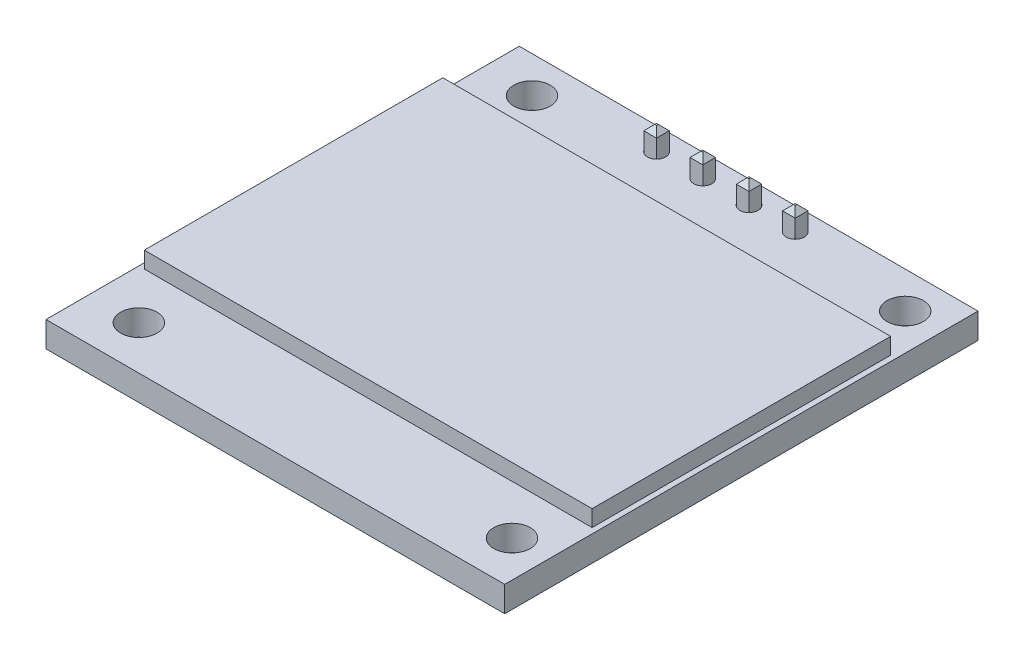
SolidWorks part; units mm, degrees
ref_plane "Front Plane" through (0, 0, 0) normal (0, 0, 1) x (1, 0, 0)
ref_plane "Top Plane" through (0, 0, 0) normal (0, 1, 0) x (1, 0, 0)
ref_plane "Right Plane" through (0, 0, 0) normal (1, 0, 0) x (0, 0, -1)
sketch "Sketch1" plane through (0, 0, 0) normal (0, 1, 0) x (1, 0, 0)
  line L0 (-3.81, 11.75) -> (3.81, 11.75) construction
  line L1 (-12.6, 13) -> (12.6, 13)
  line L2 (-12.6, 13) -> (-12.6, -13)
  line L3 (-12.6, -13) -> (12.6, -13)
  line L4 (12.6, 13) -> (12.6, -13)
  line L5 (-12.6, 13) -> (12.6, -13) construction
  line L6 (-12.6, -13) -> (12.6, 13) construction
  circle A0 centre (-9.9, 11) radius 1
  circle A1 centre (10.6, 11) radius 1
  circle A2 centre (-9.9, -10.6) radius 1
  circle A3 centre (10.6, -10.6) radius 1
  circle A4 centre (-3.81, 11.75) radius 0.5
  circle A5 centre (-1.27, 11.75) radius 0.5
  circle A6 centre (1.27, 11.75) radius 0.5
  circle A7 centre (3.81, 11.75) radius 0.5
  point P0 (0, 0)
  dimension "D3" = 2
  dimension "D8" = 1
  dimension "D10" = 4
  dimension "D1" = 25.2
  dimension "D2" = 26
  dimension "D4" = 20.5
  dimension "D5" = 21.6
  dimension "D6" = 2
  dimension "D7" = 2
  dimension "D9" = 1.25
  dimension "D11" = 3.81
extrude "Boss-Extrude1" add sketch "Sketch1" along normal blind 1.4
sketch "Sketch2" plane through (0, 1.4, 0) normal (0, 1, 0) x (1, 0, 0)
  line L0 (12.6, 13) -> (-12.6, 13) construction
  line L5 (-12.3, 8.5) -> (12.3, 8.5)
  line L6 (-12.3, 8.5) -> (-12.3, -7.9)
  line L7 (-12.3, -7.9) -> (12.3, -7.9)
  line L8 (12.3, 8.5) -> (12.3, -7.9)
  point P4 (0, 8.5)
  dimension "D1" = 16.4
  dimension "D2" = 24.6
  dimension "D3" = 4.5
extrude "Boss-Extrude2" add sketch "Sketch2" along normal blind 0.9
sketch "Sketch3" plane through (0, 0, 0) normal (0, -1, 0) x (1, 0, 0)
  line L0 (12.6, -13) -> (-12.6, -13) construction
  line L1 (5.08, -13.02) -> (-5.08, -13.02)
  line L2 (5.08, -13.02) -> (5.08, -10.48)
  line L3 (5.08, -10.48) -> (-5.08, -10.48)
  line L4 (-5.08, -13.02) -> (-5.08, -10.48)
  point P4 (0, -13.02)
  point P5 (5.08, -11.75)
  dimension "D1" = 10.16
  dimension "D2" = 2.54
  dimension "D3" = 1.25
extrude "Boss-Extrude3" add sketch "Sketch3" along normal blind 1
sketch "Sketch4" plane through (0, 0, 0) normal (0, -1, 0) x (1, 0, 0)
  line L0 (12.6, -13) -> (5.08, -13) construction
  line L1 (-3.46, -12.1) -> (-4.16, -12.1)
  line L2 (-3.46, -12.1) -> (-3.46, -11.4)
  line L3 (-3.46, -11.4) -> (-4.16, -11.4)
  line L4 (-4.16, -12.1) -> (-4.16, -11.4)
  line L5 (-0.92, -12.1) -> (-1.62, -12.1)
  line L6 (-0.92, -12.1) -> (-0.92, -11.4)
  line L7 (-0.92, -11.4) -> (-1.62, -11.4)
  line L8 (-1.62, -12.1) -> (-1.62, -11.4)
  line L9 (1.62, -12.1) -> (0.92, -12.1)
  line L10 (1.62, -12.1) -> (1.62, -11.4)
  line L11 (1.62, -11.4) -> (0.92, -11.4)
  line L12 (0.92, -12.1) -> (0.92, -11.4)
  line L13 (4.16, -12.1) -> (3.46, -12.1)
  line L14 (4.16, -12.1) -> (4.16, -11.4)
  line L15 (4.16, -11.4) -> (3.46, -11.4)
  line L16 (3.46, -12.1) -> (3.46, -11.4)
  point P6 (-3.46, -11.75)
  point P7 (-3.81, -11.4)
  dimension "D1" = 0.7
  dimension "D2" = 1.25
  dimension "D3" = 3.81
  dimension "D4" = 4
extrude "Boss-Extrude4" add sketch "Sketch4" along normal blind 8.6 and the other way blind 2.7
chamfer "Chamfer1" distance 0.3 angle 45 32 edges at (-3.81, -8.6, -12.1) (-4.16, -8.6, -11.75) (-3.81, -8.6, -11.4) (-3.46, -8.6, -11.75) (-1.27, -8.6, -12.1) (-1.62, -8.6, -11.75) (-1.27, -8.6, -11.4) (-0.92, -8.6, -11.75) (1.27, -8.6, -12.1) (0.92, -8.6, -11.75) (1.27, -8.6, -11.4) (1.62, -8.6, -11.75) (3.81, -8.6, -12.1) (3.46, -8.6, -11.75) (3.81, -8.6, -11.4) (4.16, -8.6, -11.75) (-3.81, 2.7, -11.4) (-4.16, 2.7, -11.75) (-3.81, 2.7, -12.1) (-3.46, 2.7, -11.75) (-1.27, 2.7, -11.4) (-1.62, 2.7, -11.75) (-1.27, 2.7, -12.1) (-0.92, 2.7, -11.75) (1.27, 2.7, -11.4) (0.92, 2.7, -11.75) (1.27, 2.7, -12.1) (1.62, 2.7, -11.75) (3.81, 2.7, -11.4) (3.46, 2.7, -11.75) (3.81, 2.7, -12.1) (4.16, 2.7, -11.75)
sketch "Sketch5" plane through (0, 0, 0) normal (0, -1, 0) x (1, 0, 0)
  line L0 (12.6, -13) -> (-12.6, -13) construction
  line L1 (-10.872, -6.63) -> (10.872, -6.63)
  line L2 (-10.872, -6.63) -> (-10.872, 4.234)
  line L3 (-10.872, 4.234) -> (10.872, 4.234)
  line L4 (10.872, -6.63) -> (10.872, 4.234)
  point P4 (0, -6.63)
  dimension "D1" = 21.744
  dimension "D2" = 10.864
  dimension "D3" = 6.37
extrude "Boss-Extrude5" add sketch "Sketch5" along normal blind 0.01
